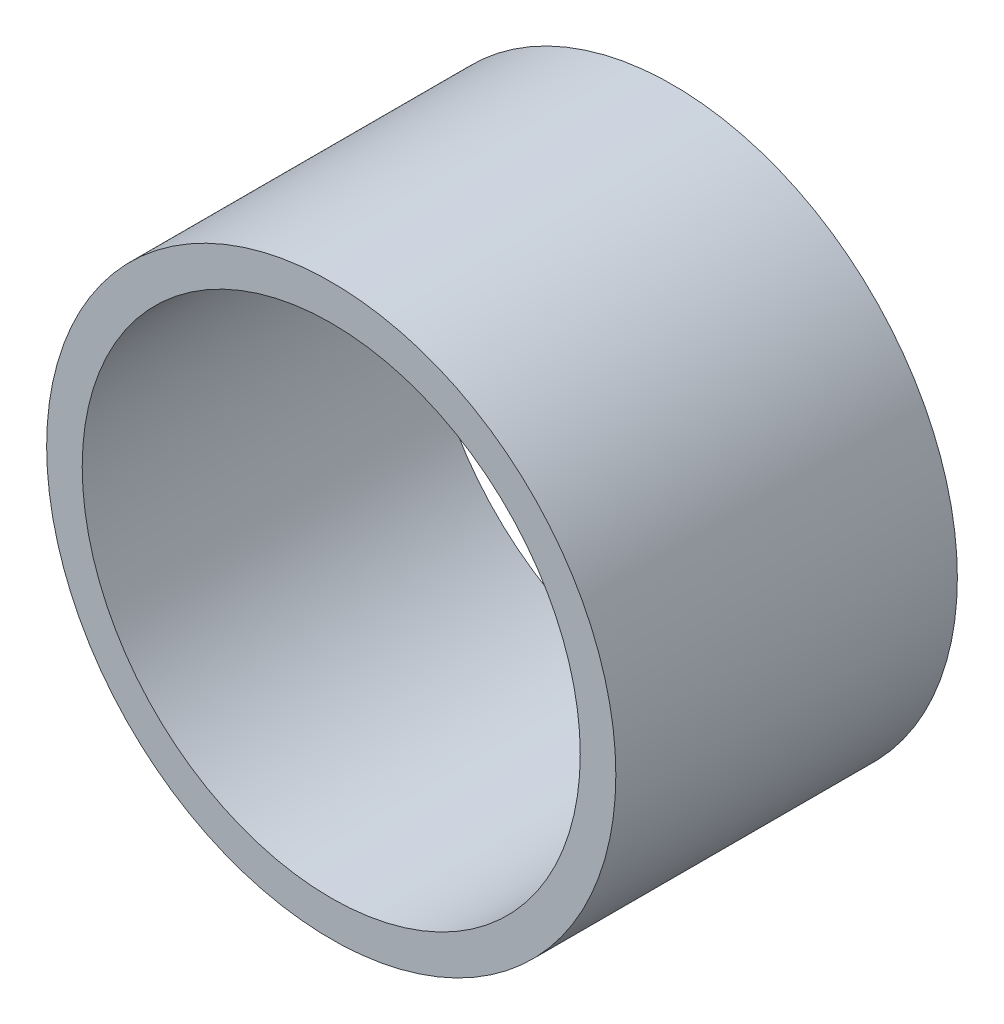
SolidWorks part; units mm, degrees
ref_plane "Front Plane" through (0, 0, 0) normal (0, 0, 1) x (1, 0, 0)
ref_plane "Top Plane" through (0, 0, 0) normal (0, 1, 0) x (1, 0, 0)
ref_plane "Right Plane" through (0, 0, 0) normal (1, 0, 0) x (0, 0, -1)
sketch "Sketch1" plane through (0, 0, 0) normal (0, 1, 0) x (1, 0, 0)
  line L0 (0, 12.5117) -> (0, 0) construction
  line L1 (8.75, 12) -> (8.75, 0)
  line L2 (8.75, 0) -> (10, 0)
  line L3 (10, 0) -> (10, 12)
  line L4 (10, 12) -> (8.75, 12)
  dimension "D1" = 12
  dimension "D2" = 20
  dimension "D3" = 1.25
revolve "Revolve1" add sketch "Sketch1" angle 360 about L0
